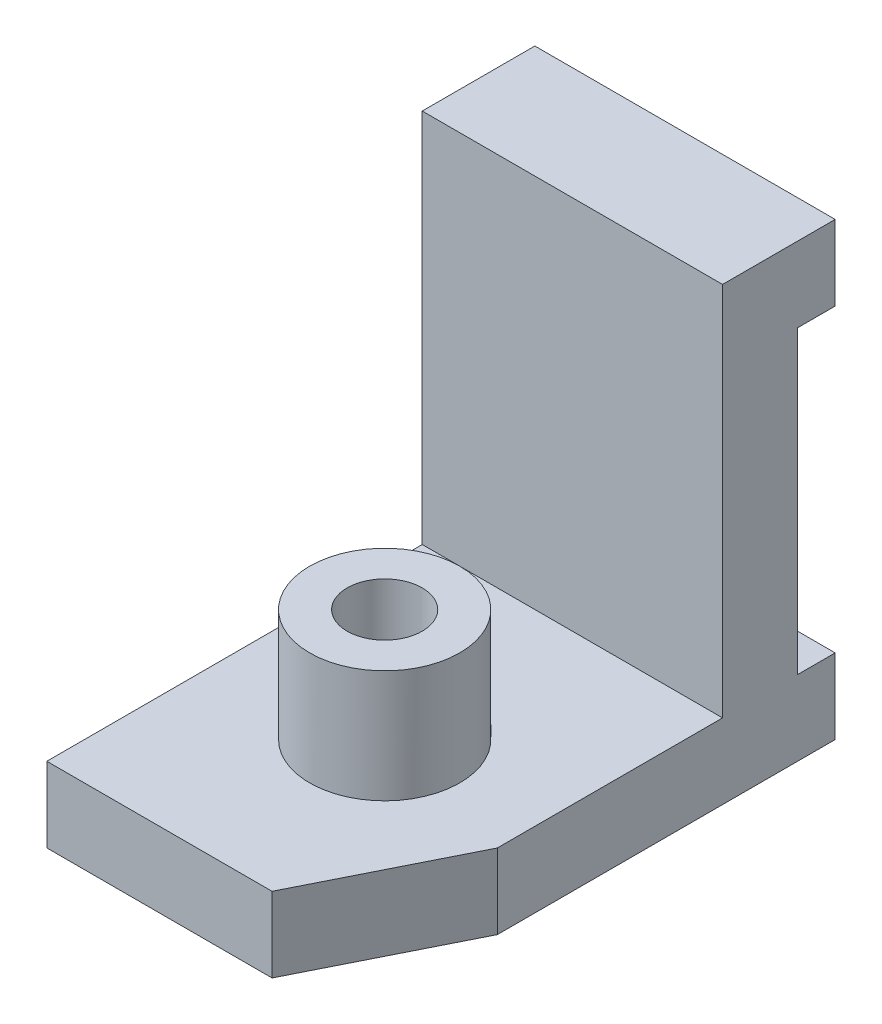
SolidWorks part; units mm, degrees
ref_plane "Front Plane" through (0, 0, 0) normal (1, 0, 0) x (0, 1, 0)
ref_plane "Top Plane" through (0, 0, 0) normal (0, 0, 1) x (0, 1, 0)
ref_plane "Right Plane" through (0, 0, 0) normal (0, 1, 0) x (-1, 0, 0)
sketch "Sketch1" plane through (0, 0, 0) normal (1, 0, 0) x (0, 1, 0)
  line L0 (0, 0) -> (0, 28554.4918) construction
  line L1 (0, 0) -> (28554.4918, 0) construction
  line L2 (0, 0) -> (10, 0)
  line L3 (10, 0) -> (10, 5)
  line L4 (10, 5) -> (50, 5)
  line L5 (50, 5) -> (50, 0)
  line L6 (50, 0) -> (60, 0)
  line L7 (60, 0) -> (60, 15)
  line L8 (60, 15) -> (10, 15)
  line L9 (10, 15) -> (10, 65)
  line L10 (10, 65) -> (0, 65)
  line L11 (0, 65) -> (0, 0)
  dimension "D1" = 60
  dimension "D2" = 40
  dimension "D3" = 5
  dimension "D4" = 10
  dimension "D5" = 15
  dimension "D6" = 65
extrude "Boss-Extrude1" add sketch "Sketch1" along normal blind 40
chamfer "Chamfer2" distance 10 distance2 20 1 edges at (40, 5, 65)
sketch "Sketch2" plane through (0, 10, 0) normal (0, 1, 0) x (-1, 0, 0)
  line L0 (-40, 15) -> (0, 15) construction
  line L1 (0, 15) -> (0, 65) construction
  circle A0 centre (-20, 40) radius 10
  circle A1 centre (-20, 40) radius 5
  dimension "D1" = 20
  dimension "D2" = 10
  dimension "D3" = 25
  dimension "D4" = 20
extrude "Boss-Extrude2" add sketch "Sketch2" along normal blind 15
